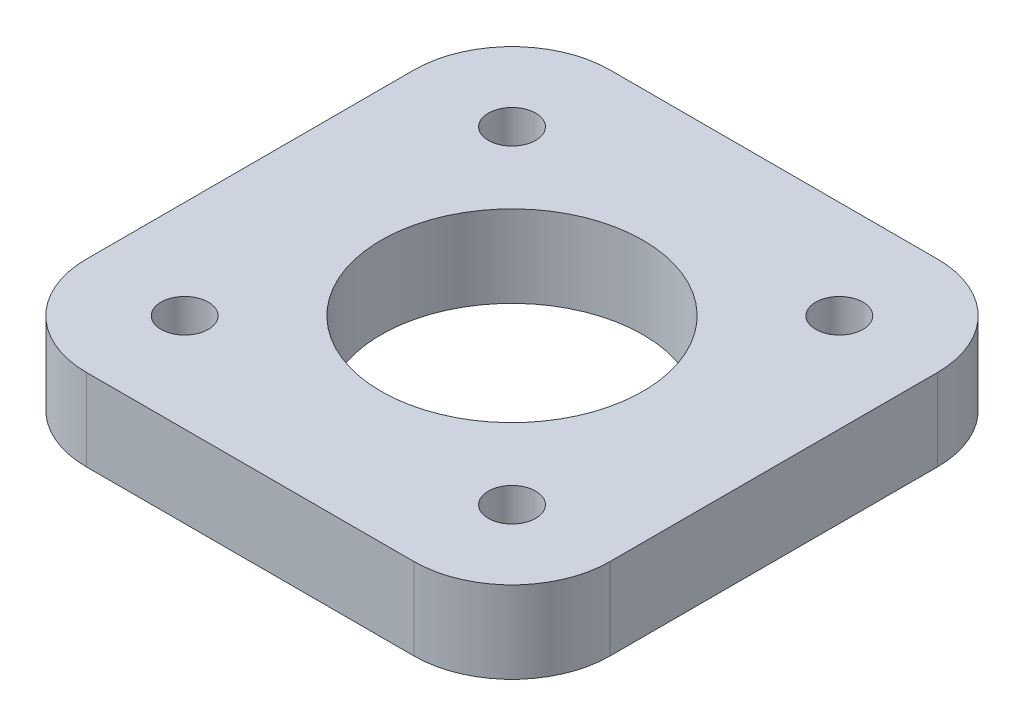
SolidWorks part; units mm, degrees
material "ABS"
ref_plane "Front Plane" through (0, 0, 0) normal (0, 0, 1) x (1, 0, 0)
ref_plane "Top Plane" through (0, 0, 0) normal (0, 1, 0) x (1, 0, 0)
ref_plane "Right Plane" through (0, 0, 0) normal (1, 0, 0) x (0, 0, -1)
sketch "Sketch1" plane through (0, 0, 0) normal (0, 1, 0) x (1, 0, 0)
  line L1 (-10, 16) -> (10, 16)
  line L2 (-16, 10) -> (-16, -10)
  line L3 (-10, -16) -> (10, -16)
  line L4 (16, 10) -> (16, -10)
  circle A0 centre (0, 0) radius 8
  circle A1 centre (-10, 10) radius 1.4457
  circle A2 centre (10, 10) radius 1.4457
  circle A3 centre (10, -10) radius 1.4457
  circle A4 centre (-10, -10) radius 1.4457
  arc A5 (-16, -10) -> (-10, -16) centre (-10, -10) ccw
  arc A6 (10, 16) -> (16, 10) centre (10, 10) cw
  arc A7 (10, -16) -> (16, -10) centre (10, -10) ccw
  arc A8 (-10, 16) -> (-16, 10) centre (-10, 10) ccw
  dimension "D1" = 16
  dimension "D2" = 2.8914
  dimension "D10" = 16
  dimension "D11" = 6
  dimension "D3" = 10
  dimension "D4" = 10
  dimension "D7" = 16
  dimension "D8" = 16
  dimension "D9" = 16
  dimension "D5" = 2
  dimension "D6" = 2
extrude "Boss-Extrude1" add sketch "Sketch1" against normal blind 5
